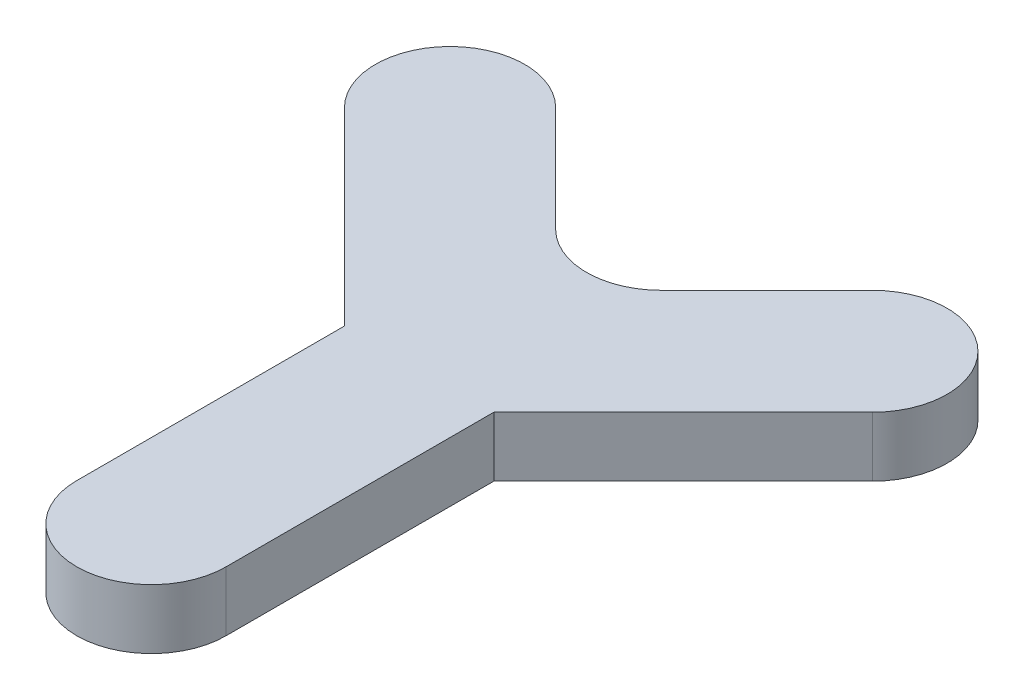
SolidWorks part; units mm, degrees
material "Copper"
ref_plane "Front Plane" through (0, 0, 0) normal (0, 0, 1) x (1, 0, 0)
ref_plane "Top Plane" through (0, 0, 0) normal (0, 1, 0) x (1, 0, 0)
ref_plane "Right Plane" through (0, 0, 0) normal (1, 0, 0) x (0, 0, -1)
sketch "Sketch1" plane through (0, 0, 0) normal (0, 1, 0) x (1, 0, 0)
  line L0 (0, 0) -> (0, -10) construction
  line L3 (0, 0) -> (7.0711, 7.0711) construction
  line L12 (0, 0) -> (-7.0711, 7.0711) construction
  line L13 (8.8388, 5.3033) -> (5.3033, 8.8388) construction
  line L14 (-8.8388, 5.3033) -> (-5.3033, 8.8388) construction
  line L15 (2.5, -10) -> (2.5, -1.0355)
  line L16 (8.8388, 5.3033) -> (2.5, -1.0355)
  line L17 (-2.5, -10) -> (-2.5, -1.0355)
  line L18 (-2.5, -1.0355) -> (-8.8388, 5.3033)
  line L19 (-5.3033, 8.8388) -> (-1.7678, 5.3033)
  line L20 (1.7678, 5.3033) -> (5.3033, 8.8388)
  arc A0 (8.8388, 5.3033) -> (5.3033, 8.8388) centre (7.0711, 7.0711) ccw
  arc A1 (-2.5, -10) -> (2.5, -10) centre (0, -10) ccw
  arc A2 (-5.3033, 8.8388) -> (-8.8388, 5.3033) centre (-7.0711, 7.0711) ccw
  arc A4 (-1.7678, 5.3033) -> (1.7678, 5.3033) centre (0, 7.0711) ccw
  dimension "D5" = 5
  dimension "D6" = 2.5
  dimension "D7" = 2.5
  dimension "D2" = 135
  dimension "D3" = 10
  dimension "D4" = 10
extrude "Boss-Extrude1" add sketch "Sketch1" along normal blind 2
